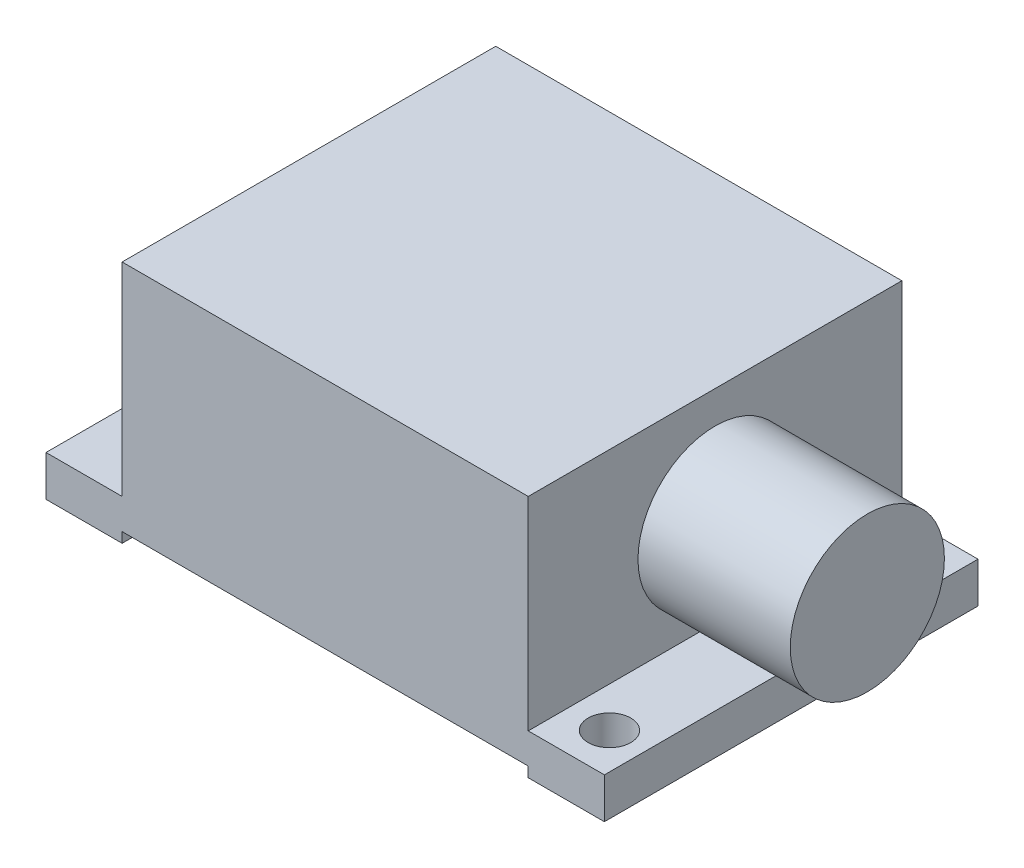
SolidWorks part; units mm, degrees
ref_plane "前视基准面" through (0, 0, 0) normal (0, 0, 1) x (1, 0, 0)
ref_plane "上视基准面" through (0, 0, 0) normal (0, 1, 0) x (1, 0, 0)
ref_plane "右视基准面" through (0, 0, 0) normal (1, 0, 0) x (0, 0, -1)
sketch "草图1" plane through (0, 0, 0) normal (0, 1, 0) x (1, 0, 0)
  line L1 (-27.5, 18.4) -> (27.5, 18.4)
  line L2 (-27.5, 18.4) -> (-27.5, -18.4)
  line L3 (-27.5, -18.4) -> (27.5, -18.4)
  line L4 (27.5, 18.4) -> (27.5, -18.4)
  line L5 (-27.5, 18.4) -> (27.5, -18.4) construction
  line L6 (-27.5, -18.4) -> (27.5, 18.4) construction
  point P0 (0, 0)
  dimension "D1" = 36.8
  dimension "D2" = 55
extrude "凸台-拉伸1" add sketch "草图1" along normal blind 4
sketch "草图2" plane through (0, 4, 0) normal (0, 1, 0) x (1, 0, 0)
  line L1 (-20, 18.4) -> (20, 18.4)
  line L2 (-20, 18.4) -> (-20, -18.4)
  line L3 (-20, -18.4) -> (20, -18.4)
  line L4 (20, 18.4) -> (20, -18.4)
  line L5 (-20, 18.4) -> (20, -18.4) construction
  line L6 (-20, -18.4) -> (20, 18.4) construction
  point P0 (0, 0)
  dimension "D1" = 40
  dimension "D2" = 36.8
extrude "凸台-拉伸2" add sketch "草图2" along normal blind 20
sketch "草图3" plane through (0, 0, 18.4) normal (0, 0, 1) x (1, 0, 0)
  line L0 (-27.5, 0) -> (27.5, 0) construction
  line L1 (-20, 1) -> (20, 1)
  line L2 (-20, 1) -> (-20, -1)
  line L3 (-20, -1) -> (20, -1)
  line L4 (20, 1) -> (20, -1)
  line L5 (-20, 1) -> (20, -1) construction
  line L6 (-20, -1) -> (20, 1) construction
  point P0 (0, 0)
  dimension "D1" = 1
  dimension "D2" = 40
extrude "切除-拉伸1" cut sketch "草图3" against normal blind 200
sketch "草图4" plane through (0, 4, 0) normal (0, 1, 0) x (1, 0, 0)
  line L0 (-43.9121, 0) -> (44.1154, 0) construction
  line L1 (0, 28.2583) -> (0, -25.6561) construction
  circle A0 centre (-23.95, 0) radius 2.1
  circle A1 centre (23.95, 14.35) radius 2.1
  circle A2 centre (23.95, -14.35) radius 2.1
  dimension "D1" = 4.2
  dimension "D2" = 47.9
  dimension "D3" = 47.9
  dimension "D4" = 14.35
  dimension "D5" = 28.7
  dimension "D6" = 23.95
extrude "切除-拉伸2" cut sketch "草图4" against normal blind 200
sketch "草图5" plane through (20, 0, 0) normal (1, 0, 0) x (0, 0, -1)
  circle A0 centre (0, 13.2144) radius 7.5919
extrude "凸台-拉伸3" add sketch "草图5" along normal blind 15
